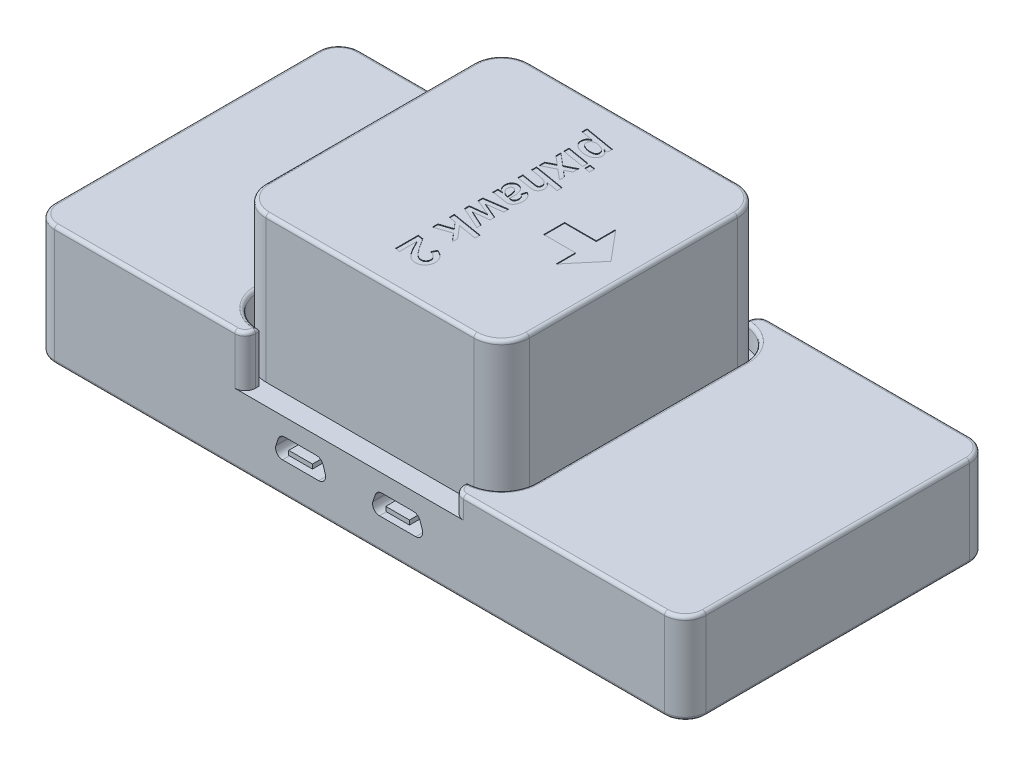
SolidWorks part; units mm, degrees
ref_plane "Front Plane" through (0, 0, 0) normal (0, 0, 1) x (1, 0, 0)
ref_plane "Top Plane" through (0, 0, 0) normal (0, 1, 0) x (1, 0, 0)
ref_plane "Right Plane" through (0, 0, 0) normal (1, 0, 0) x (0, 0, -1)
sketch "Sketch1" plane through (0, 0, 0) normal (0, 1, 0) x (1, 0, 0)
  line L1 (-44, 22) -> (44, 22)
  line L2 (-47, 19) -> (-47, -19)
  line L3 (-44, -22) -> (44, -22)
  line L4 (47, 19) -> (47, -19)
  line L5 (-47, 22) -> (47, -22) construction
  line L6 (-47, -22) -> (47, 22) construction
  arc A0 (44, 22) -> (47, 19) centre (44, 19) cw
  arc A1 (-47, -19) -> (-44, -22) centre (-44, -19) ccw
  arc A2 (-44, 22) -> (-47, 19) centre (-44, 19) ccw
  arc A3 (44, -22) -> (47, -19) centre (44, -19) ccw
  point P0 (0, 0)
  dimension "D3" = 3
  dimension "D1" = 94
  dimension "D2" = 44
extrude "Boss-Extrude1" add sketch "Sketch1" along normal blind 10
sketch "Sketch2" plane through (0, 10, 0) normal (0, 1, 0) x (1, 0, 0)
  line L1 (-16.5, 20) -> (13.5, 20)
  line L2 (-21.5, 15) -> (-21.5, -15)
  line L3 (-16.5, -20) -> (13.5, -20)
  line L4 (18.5, 15) -> (18.5, -15)
  line L5 (-21.5, 20) -> (18.5, -20) construction
  line L6 (-21.5, -20) -> (18.5, 20) construction
  line L7 (-47, 0) -> (0, 0) construction
  line L8 (-47, 19) -> (-47, -19) construction
  line L9 (0, 0) -> (0, 22) construction
  line L10 (44, 22) -> (-44, 22) construction
  arc A0 (13.5, 20) -> (18.5, 15) centre (13.5, 15) cw
  arc A1 (-21.5, -15) -> (-16.5, -20) centre (-16.5, -15) ccw
  arc A2 (-16.5, 20) -> (-21.5, 15) centre (-16.5, 15) ccw
  arc A3 (13.5, -20) -> (18.5, -15) centre (13.5, -15) ccw
  point P0 (-1.5, 0)
  dimension "D4" = 5
  dimension "D1" = 40
  dimension "D2" = 40
  dimension "D3" = 25.5
sketch "Sketch3" plane through (0, 10, 0) normal (0, 1, 0) x (1, 0, 0)
  line L0 (18.5, 15) -> (18.5, -15) construction
  line L1 (44, 22) -> (-44, 22) construction
  line L2 (47, -19) -> (47, 19) construction
  line L3 (-44, -22) -> (44, -22) construction
  line L4 (18.5, 15) -> (18.5, -15)
  line L5 (44, 22) -> (13.5, 22)
  line L6 (47, -19) -> (47, 19)
  line L7 (13.5, -22) -> (44, -22)
  line L8 (13.5, 20) -> (13.5, 22)
  line L9 (13.5, -20) -> (13.5, -22)
  arc A0 (18.5, 15) -> (13.5, 20) centre (13.5, 15) ccw construction
  arc A1 (13.5, -20) -> (18.5, -15) centre (13.5, -15) ccw construction
  arc A2 (47, 19) -> (44, 22) centre (44, 19) ccw construction
  arc A3 (44, -22) -> (47, -19) centre (44, -19) ccw construction
  arc A4 (18.5, 15) -> (13.5, 20) centre (13.5, 15) ccw
  arc A5 (13.5, -20) -> (18.5, -15) centre (13.5, -15) ccw
  arc A6 (47, 19) -> (44, 22) centre (44, 19) ccw
  arc A7 (44, -22) -> (47, -19) centre (44, -19) ccw
extrude "Boss-Extrude2" add sketch "Sketch3" along normal blind 3.1
sketch "Sketch4" plane through (0, 10, 0) normal (0, 1, 0) x (1, 0, 0)
  line L0 (-21.5, 15) -> (-21.5, -15) construction
  line L1 (-44, -22) -> (13.5, -22) construction
  line L2 (-47, 19) -> (-47, -19) construction
  line L3 (13.5, 22) -> (-44, 22) construction
  line L4 (-21.5, 15) -> (-21.5, -15)
  line L5 (-44, -22) -> (-16.5, -22)
  line L6 (-47, 19) -> (-47, -19)
  line L7 (-16.5, 22) -> (-44, 22)
  line L8 (-16.5, 20) -> (-16.5, 22)
  line L9 (-16.5, -20) -> (-16.5, -22)
  arc A0 (-16.5, 20) -> (-21.5, 15) centre (-16.5, 15) ccw construction
  arc A1 (-21.5, -15) -> (-16.5, -20) centre (-16.5, -15) ccw construction
  arc A2 (-47, -19) -> (-44, -22) centre (-44, -19) ccw construction
  arc A3 (-44, 22) -> (-47, 19) centre (-44, 19) ccw construction
  arc A4 (-16.5, 20) -> (-21.5, 15) centre (-16.5, 15) ccw
  arc A5 (-21.5, -15) -> (-16.5, -20) centre (-16.5, -15) ccw
  arc A6 (-47, -19) -> (-44, -22) centre (-44, -19) ccw
  arc A7 (-44, 22) -> (-47, 19) centre (-44, 19) ccw
extrude "Boss-Extrude3" add sketch "Sketch4" along normal blind 7.3
fillet "Fillet1" radius 1.5 4 edges at (-16.5, 13.65, -22) (-16.5, 13.65, 22)
sketch "Sketch5" plane through (0, 10, 0) normal (0, 1, 0) x (1, 0, 0)
  line L24 (-16.5, -19) -> (13.5, -19)
  line L25 (17.5, -15) -> (17.5, 15)
  line L26 (13.5, 19) -> (-16.5, 19)
  line L27 (-20.5, 15) -> (-20.5, -15)
  line L28 (-16.5, -19) -> (13.5, -19)
  line L29 (17.5, -15) -> (17.5, 15)
  line L30 (13.5, 19) -> (-16.5, 19)
  line L31 (-20.5, 15) -> (-20.5, -15)
  arc A20 (-20.5, -15) -> (-16.5, -19) centre (-16.5, -15) ccw
  arc A21 (13.5, -19) -> (17.5, -15) centre (13.5, -15) ccw
  arc A22 (17.5, 15) -> (13.5, 19) centre (13.5, 15) ccw
  arc A23 (-16.5, 19) -> (-20.5, 15) centre (-16.5, 15) ccw
  arc A24 (-20.5, -15) -> (-16.5, -19) centre (-16.5, -15) ccw
  arc A25 (13.5, -19) -> (17.5, -15) centre (13.5, -15) ccw
  arc A26 (17.5, 15) -> (13.5, 19) centre (13.5, 15) ccw
  arc A27 (-16.5, 19) -> (-20.5, 15) centre (-16.5, 15) ccw
  dimension "D1" = 1
extrude "Boss-Extrude4" add sketch "Sketch5" along normal blind 21
fillet "Fillet2" radius 0.5 40 edges at (0, 0, -22) (-46.1213, 0, -21.1213) (-47, 0, 0) (-46.1213, 0, 21.1213) (0, 0, 22) (46.1213, 0, 21.1213) (47, 0, 0) (46.1213, 0, -21.1213) (-20.0355, 17.3, -18.5355) (-21.5, 17.3, 0) (-20.0355, 17.3, 18.5355) (-16.5, 17.3, 20.25) (-16.9393, 17.3, 21.5607) (-31, 17.3, 22) (-46.1213, 17.3, 21.1213) (-47, 17.3, 0) (-46.1213, 17.3, -21.1213) (-31, 17.3, -22) (-16.9393, 17.3, -21.5607) (-16.5, 17.3, -20.25) (46.1213, 13.1, -21.1213) (47, 13.1, 0) (46.1213, 13.1, 21.1213) (29.5, 13.1, 22) (13.9393, 13.1, 21.5607) (13.5, 13.1, 20.25) (17.0355, 13.1, 18.5355) (18.5, 13.1, 0) (17.0355, 13.1, -18.5355) (13.5, 13.1, -20.25) (13.9393, 13.1, -21.5607) (29.5, 13.1, -22) (-20.5, 31, 0) (-19.3284, 31, -17.8284) (-1.5, 31, -19) (16.3284, 31, -17.8284) (17.5, 31, 0) (16.3284, 31, 17.8284) (-1.5, 31, 19) (-19.3284, 31, 17.8284)
sketch "Sketch6" plane through (-47, 0, 0) normal (-1, 0, 0) x (0, 0, 1)
  line L0 (-19, 16) -> (-19, 7.2)
  line L1 (-19, 7.2) -> (-18, 7.2)
  line L2 (-18, 7.2) -> (-18, 8)
  line L3 (-18, 8) -> (-17, 8)
  line L4 (-3, 8) -> (-3, 7.2)
  line L5 (-17, 16) -> (-19, 16)
  line L6 (-19, 17.3) -> (19, 17.3) construction
  line L7 (-22, 16.8) -> (-22, 0.5) construction
  line L8 (-17, 12) -> (-19, 12) construction
  line L9 (-18.375, 14.125) -> (-17.625, 14.125)
  line L10 (-18.375, 12.375) -> (-17.625, 12.375)
  line L11 (-18.375, 12.375) -> (-18.375, 11.625)
  line L12 (-18.375, 11.625) -> (-17.625, 11.625)
  line L13 (-17.625, 12.375) -> (-17.625, 11.625)
  line L14 (-18.375, 12.375) -> (-17.625, 11.625) construction
  line L15 (-18.375, 11.625) -> (-17.625, 12.375) construction
  line L16 (-18.375, 14.875) -> (-18.375, 14.125)
  line L17 (-18.375, 14.875) -> (-17.625, 14.875)
  line L18 (-17.625, 14.875) -> (-17.625, 14.125)
  line L19 (-17.625, 9.125) -> (-17.625, 9.875)
  line L20 (-18.375, 9.125) -> (-17.625, 9.125)
  line L21 (-18.375, 9.125) -> (-18.375, 9.875)
  line L22 (-18.375, 9.875) -> (-17.625, 9.875)
  line L23 (-1, 8) -> (-1, 7.2)
  line L24 (-17, 7.2) -> (-16, 7.2)
  line L25 (-16, 7.2) -> (-16, 8)
  line L26 (-16, 8) -> (-15, 8)
  line L27 (1, 8) -> (1, 7.2)
  line L28 (-15, 16) -> (-17, 16)
  line L29 (-16.375, 14.125) -> (-15.625, 14.125)
  line L30 (-16.375, 12.375) -> (-15.625, 12.375)
  line L31 (-16.375, 12.375) -> (-16.375, 11.625)
  line L32 (-16.375, 11.625) -> (-15.625, 11.625)
  line L33 (-15.625, 12.375) -> (-15.625, 11.625)
  line L34 (-16.375, 14.875) -> (-16.375, 14.125)
  line L35 (-16.375, 14.875) -> (-15.625, 14.875)
  line L36 (-15.625, 14.875) -> (-15.625, 14.125)
  line L37 (-15.625, 9.125) -> (-15.625, 9.875)
  line L38 (-16.375, 9.125) -> (-15.625, 9.125)
  line L39 (-16.375, 9.125) -> (-16.375, 9.875)
  line L40 (-16.375, 9.875) -> (-15.625, 9.875)
  line L41 (-15, 12) -> (-17, 12) construction
  line L42 (-16.375, 12.375) -> (-15.625, 11.625) construction
  line L43 (-16.375, 11.625) -> (-15.625, 12.375) construction
  line L44 (-15, 8) -> (-15, 7.2)
  line L45 (-15, 7.2) -> (-14, 7.2)
  line L46 (-14, 7.2) -> (-14, 8)
  line L47 (-14, 8) -> (-13, 8)
  line L48 (3, 8) -> (3, 7.2)
  line L49 (-13, 16) -> (-15, 16)
  line L50 (-14.375, 14.125) -> (-13.625, 14.125)
  line L51 (-14.375, 12.375) -> (-13.625, 12.375)
  line L52 (-14.375, 12.375) -> (-14.375, 11.625)
  line L53 (-14.375, 11.625) -> (-13.625, 11.625)
  line L54 (-13.625, 12.375) -> (-13.625, 11.625)
  line L55 (-14.375, 14.875) -> (-14.375, 14.125)
  line L56 (-14.375, 14.875) -> (-13.625, 14.875)
  line L57 (-13.625, 14.875) -> (-13.625, 14.125)
  line L58 (-13.625, 9.125) -> (-13.625, 9.875)
  line L59 (-14.375, 9.125) -> (-13.625, 9.125)
  line L60 (-14.375, 9.125) -> (-14.375, 9.875)
  line L61 (-14.375, 9.875) -> (-13.625, 9.875)
  line L62 (-13, 12) -> (-15, 12) construction
  line L63 (-14.375, 12.375) -> (-13.625, 11.625) construction
  line L64 (-14.375, 11.625) -> (-13.625, 12.375) construction
  line L65 (-13, 8) -> (-13, 7.2)
  line L66 (-13, 7.2) -> (-12, 7.2)
  line L67 (-12, 7.2) -> (-12, 8)
  line L68 (-12, 8) -> (-11, 8)
  line L69 (5, 8) -> (5, 7.2)
  line L70 (-11, 16) -> (-13, 16)
  line L71 (-12.375, 14.125) -> (-11.625, 14.125)
  line L72 (-12.375, 12.375) -> (-11.625, 12.375)
  line L73 (-12.375, 12.375) -> (-12.375, 11.625)
  line L74 (-12.375, 11.625) -> (-11.625, 11.625)
  line L75 (-11.625, 12.375) -> (-11.625, 11.625)
  line L76 (-12.375, 14.875) -> (-12.375, 14.125)
  line L77 (-12.375, 14.875) -> (-11.625, 14.875)
  line L78 (-11.625, 14.875) -> (-11.625, 14.125)
  line L79 (-11.625, 9.125) -> (-11.625, 9.875)
  line L80 (-12.375, 9.125) -> (-11.625, 9.125)
  line L81 (-12.375, 9.125) -> (-12.375, 9.875)
  line L82 (-12.375, 9.875) -> (-11.625, 9.875)
  line L83 (-11, 12) -> (-13, 12) construction
  line L84 (-12.375, 12.375) -> (-11.625, 11.625) construction
  line L85 (-12.375, 11.625) -> (-11.625, 12.375) construction
  line L86 (-11, 8) -> (-11, 7.2)
  line L87 (-11, 7.2) -> (-10, 7.2)
  line L88 (-10, 7.2) -> (-10, 8)
  line L89 (-10, 8) -> (-9, 8)
  line L90 (7, 8) -> (7, 7.2)
  line L91 (-9, 16) -> (-11, 16)
  line L92 (-10.375, 14.125) -> (-9.625, 14.125)
  line L93 (-10.375, 12.375) -> (-9.625, 12.375)
  line L94 (-10.375, 12.375) -> (-10.375, 11.625)
  line L95 (-10.375, 11.625) -> (-9.625, 11.625)
  line L96 (-9.625, 12.375) -> (-9.625, 11.625)
  line L97 (-10.375, 14.875) -> (-10.375, 14.125)
  line L98 (-10.375, 14.875) -> (-9.625, 14.875)
  line L99 (-9.625, 14.875) -> (-9.625, 14.125)
  line L100 (-9.625, 9.125) -> (-9.625, 9.875)
  line L101 (-10.375, 9.125) -> (-9.625, 9.125)
  line L102 (-10.375, 9.125) -> (-10.375, 9.875)
  line L103 (-10.375, 9.875) -> (-9.625, 9.875)
  line L104 (-9, 12) -> (-11, 12) construction
  line L105 (-10.375, 12.375) -> (-9.625, 11.625) construction
  line L106 (-10.375, 11.625) -> (-9.625, 12.375) construction
  line L107 (-9, 8) -> (-9, 7.2)
  line L108 (-9, 7.2) -> (-8, 7.2)
  line L109 (-8, 7.2) -> (-8, 8)
  line L110 (-8, 8) -> (-7, 8)
  line L111 (9, 8) -> (9, 7.2)
  line L112 (-7, 16) -> (-9, 16)
  line L113 (-8.375, 14.125) -> (-7.625, 14.125)
  line L114 (-8.375, 12.375) -> (-7.625, 12.375)
  line L115 (-8.375, 12.375) -> (-8.375, 11.625)
  line L116 (-8.375, 11.625) -> (-7.625, 11.625)
  line L117 (-7.625, 12.375) -> (-7.625, 11.625)
  line L118 (-8.375, 14.875) -> (-8.375, 14.125)
  line L119 (-8.375, 14.875) -> (-7.625, 14.875)
  line L120 (-7.625, 14.875) -> (-7.625, 14.125)
  line L121 (-7.625, 9.125) -> (-7.625, 9.875)
  line L122 (-8.375, 9.125) -> (-7.625, 9.125)
  line L123 (-8.375, 9.125) -> (-8.375, 9.875)
  line L124 (-8.375, 9.875) -> (-7.625, 9.875)
  line L125 (-7, 12) -> (-9, 12) construction
  line L126 (-8.375, 12.375) -> (-7.625, 11.625) construction
  line L127 (-8.375, 11.625) -> (-7.625, 12.375) construction
  line L128 (-7, 8) -> (-7, 7.2)
  line L129 (-7, 7.2) -> (-6, 7.2)
  line L130 (-6, 7.2) -> (-6, 8)
  line L131 (-6, 8) -> (-5, 8)
  line L132 (11, 8) -> (11, 7.2)
  line L133 (-5, 16) -> (-7, 16)
  line L134 (-6.375, 14.125) -> (-5.625, 14.125)
  line L135 (-6.375, 12.375) -> (-5.625, 12.375)
  line L136 (-6.375, 12.375) -> (-6.375, 11.625)
  line L137 (-6.375, 11.625) -> (-5.625, 11.625)
  line L138 (-5.625, 12.375) -> (-5.625, 11.625)
  line L139 (-6.375, 14.875) -> (-6.375, 14.125)
  line L140 (-6.375, 14.875) -> (-5.625, 14.875)
  line L141 (-5.625, 14.875) -> (-5.625, 14.125)
  line L142 (-5.625, 9.125) -> (-5.625, 9.875)
  line L143 (-6.375, 9.125) -> (-5.625, 9.125)
  line L144 (-6.375, 9.125) -> (-6.375, 9.875)
  line L145 (-6.375, 9.875) -> (-5.625, 9.875)
  line L146 (-5, 12) -> (-7, 12) construction
  line L147 (-6.375, 12.375) -> (-5.625, 11.625) construction
  line L148 (-6.375, 11.625) -> (-5.625, 12.375) construction
  line L149 (-5, 8) -> (-5, 7.2)
  line L150 (-5, 7.2) -> (-4, 7.2)
  line L151 (-4, 7.2) -> (-4, 8)
  line L152 (-4, 8) -> (-3, 8)
  line L154 (-3, 16) -> (-5, 16)
  line L155 (-4.375, 14.125) -> (-3.625, 14.125)
  line L156 (-4.375, 12.375) -> (-3.625, 12.375)
  line L157 (-4.375, 12.375) -> (-4.375, 11.625)
  line L158 (-4.375, 11.625) -> (-3.625, 11.625)
  line L159 (-3.625, 12.375) -> (-3.625, 11.625)
  line L160 (-4.375, 14.875) -> (-4.375, 14.125)
  line L161 (-4.375, 14.875) -> (-3.625, 14.875)
  line L162 (-3.625, 14.875) -> (-3.625, 14.125)
  line L163 (-3.625, 9.125) -> (-3.625, 9.875)
  line L164 (-4.375, 9.125) -> (-3.625, 9.125)
  line L165 (-4.375, 9.125) -> (-4.375, 9.875)
  line L166 (-4.375, 9.875) -> (-3.625, 9.875)
  line L167 (-3, 12) -> (-5, 12) construction
  line L168 (-4.375, 12.375) -> (-3.625, 11.625) construction
  line L169 (-4.375, 11.625) -> (-3.625, 12.375) construction
  line L171 (-3, 7.2) -> (-2, 7.2)
  line L172 (-2, 7.2) -> (-2, 8)
  line L173 (-2, 8) -> (-1, 8)
  line L175 (-1, 16) -> (-3, 16)
  line L176 (-2.375, 14.125) -> (-1.625, 14.125)
  line L177 (-2.375, 12.375) -> (-1.625, 12.375)
  line L178 (-2.375, 12.375) -> (-2.375, 11.625)
  line L179 (-2.375, 11.625) -> (-1.625, 11.625)
  line L180 (-1.625, 12.375) -> (-1.625, 11.625)
  line L181 (-2.375, 14.875) -> (-2.375, 14.125)
  line L182 (-2.375, 14.875) -> (-1.625, 14.875)
  line L183 (-1.625, 14.875) -> (-1.625, 14.125)
  line L184 (-1.625, 9.125) -> (-1.625, 9.875)
  line L185 (-2.375, 9.125) -> (-1.625, 9.125)
  line L186 (-2.375, 9.125) -> (-2.375, 9.875)
  line L187 (-2.375, 9.875) -> (-1.625, 9.875)
  line L188 (-1, 12) -> (-3, 12) construction
  line L189 (-2.375, 12.375) -> (-1.625, 11.625) construction
  line L190 (-2.375, 11.625) -> (-1.625, 12.375) construction
  line L192 (-1, 7.2) -> (0, 7.2)
  line L193 (0, 7.2) -> (0, 8)
  line L194 (0, 8) -> (1, 8)
  line L196 (1, 16) -> (-1, 16)
  line L197 (-0.375, 14.125) -> (0.375, 14.125)
  line L198 (-0.375, 12.375) -> (0.375, 12.375)
  line L199 (-0.375, 12.375) -> (-0.375, 11.625)
  line L200 (-0.375, 11.625) -> (0.375, 11.625)
  line L201 (0.375, 12.375) -> (0.375, 11.625)
  line L202 (-0.375, 14.875) -> (-0.375, 14.125)
  line L203 (-0.375, 14.875) -> (0.375, 14.875)
  line L204 (0.375, 14.875) -> (0.375, 14.125)
  line L205 (0.375, 9.125) -> (0.375, 9.875)
  line L206 (-0.375, 9.125) -> (0.375, 9.125)
  line L207 (-0.375, 9.125) -> (-0.375, 9.875)
  line L208 (-0.375, 9.875) -> (0.375, 9.875)
  line L209 (1, 12) -> (-1, 12) construction
  line L210 (-0.375, 12.375) -> (0.375, 11.625) construction
  line L211 (-0.375, 11.625) -> (0.375, 12.375) construction
  line L213 (1, 7.2) -> (2, 7.2)
  line L214 (2, 7.2) -> (2, 8)
  line L215 (2, 8) -> (3, 8)
  line L217 (3, 16) -> (1, 16)
  line L218 (1.625, 14.125) -> (2.375, 14.125)
  line L219 (1.625, 12.375) -> (2.375, 12.375)
  line L220 (1.625, 12.375) -> (1.625, 11.625)
  line L221 (1.625, 11.625) -> (2.375, 11.625)
  line L222 (2.375, 12.375) -> (2.375, 11.625)
  line L223 (1.625, 14.875) -> (1.625, 14.125)
  line L224 (1.625, 14.875) -> (2.375, 14.875)
  line L225 (2.375, 14.875) -> (2.375, 14.125)
  line L226 (2.375, 9.125) -> (2.375, 9.875)
  line L227 (1.625, 9.125) -> (2.375, 9.125)
  line L228 (1.625, 9.125) -> (1.625, 9.875)
  line L229 (1.625, 9.875) -> (2.375, 9.875)
  line L230 (3, 12) -> (1, 12) construction
  line L231 (1.625, 12.375) -> (2.375, 11.625) construction
  line L232 (1.625, 11.625) -> (2.375, 12.375) construction
  line L234 (3, 7.2) -> (4, 7.2)
  line L235 (4, 7.2) -> (4, 8)
  line L236 (4, 8) -> (5, 8)
  line L238 (5, 16) -> (3, 16)
  line L239 (3.625, 14.125) -> (4.375, 14.125)
  line L240 (3.625, 12.375) -> (4.375, 12.375)
  line L241 (3.625, 12.375) -> (3.625, 11.625)
  line L242 (3.625, 11.625) -> (4.375, 11.625)
  line L243 (4.375, 12.375) -> (4.375, 11.625)
  line L244 (3.625, 14.875) -> (3.625, 14.125)
  line L245 (3.625, 14.875) -> (4.375, 14.875)
  line L246 (4.375, 14.875) -> (4.375, 14.125)
  line L247 (4.375, 9.125) -> (4.375, 9.875)
  line L248 (3.625, 9.125) -> (4.375, 9.125)
  line L249 (3.625, 9.125) -> (3.625, 9.875)
  line L250 (3.625, 9.875) -> (4.375, 9.875)
  line L251 (5, 12) -> (3, 12) construction
  line L252 (3.625, 12.375) -> (4.375, 11.625) construction
  line L253 (3.625, 11.625) -> (4.375, 12.375) construction
  line L255 (5, 7.2) -> (6, 7.2)
  line L256 (6, 7.2) -> (6, 8)
  line L257 (6, 8) -> (7, 8)
  line L259 (7, 16) -> (5, 16)
  line L260 (5.625, 14.125) -> (6.375, 14.125)
  line L261 (5.625, 12.375) -> (6.375, 12.375)
  line L262 (5.625, 12.375) -> (5.625, 11.625)
  line L263 (5.625, 11.625) -> (6.375, 11.625)
  line L264 (6.375, 12.375) -> (6.375, 11.625)
  line L265 (5.625, 14.875) -> (5.625, 14.125)
  line L266 (5.625, 14.875) -> (6.375, 14.875)
  line L267 (6.375, 14.875) -> (6.375, 14.125)
  line L268 (6.375, 9.125) -> (6.375, 9.875)
  line L269 (5.625, 9.125) -> (6.375, 9.125)
  line L270 (5.625, 9.125) -> (5.625, 9.875)
  line L271 (5.625, 9.875) -> (6.375, 9.875)
  line L272 (7, 12) -> (5, 12) construction
  line L273 (5.625, 12.375) -> (6.375, 11.625) construction
  line L274 (5.625, 11.625) -> (6.375, 12.375) construction
  line L276 (7, 7.2) -> (8, 7.2)
  line L277 (8, 7.2) -> (8, 8)
  line L278 (8, 8) -> (9, 8)
  line L280 (9, 16) -> (7, 16)
  line L281 (7.625, 14.125) -> (8.375, 14.125)
  line L282 (7.625, 12.375) -> (8.375, 12.375)
  line L283 (7.625, 12.375) -> (7.625, 11.625)
  line L284 (7.625, 11.625) -> (8.375, 11.625)
  line L285 (8.375, 12.375) -> (8.375, 11.625)
  line L286 (7.625, 14.875) -> (7.625, 14.125)
  line L287 (7.625, 14.875) -> (8.375, 14.875)
  line L288 (8.375, 14.875) -> (8.375, 14.125)
  line L289 (8.375, 9.125) -> (8.375, 9.875)
  line L290 (7.625, 9.125) -> (8.375, 9.125)
  line L291 (7.625, 9.125) -> (7.625, 9.875)
  line L292 (7.625, 9.875) -> (8.375, 9.875)
  line L293 (9, 12) -> (7, 12) construction
  line L294 (7.625, 12.375) -> (8.375, 11.625) construction
  line L295 (7.625, 11.625) -> (8.375, 12.375) construction
  line L297 (9, 7.2) -> (10, 7.2)
  line L298 (10, 7.2) -> (10, 8)
  line L299 (10, 8) -> (11, 8)
  line L301 (11, 16) -> (9, 16)
  line L302 (9.625, 14.125) -> (10.375, 14.125)
  line L303 (9.625, 12.375) -> (10.375, 12.375)
  line L304 (9.625, 12.375) -> (9.625, 11.625)
  line L305 (9.625, 11.625) -> (10.375, 11.625)
  line L306 (10.375, 12.375) -> (10.375, 11.625)
  line L307 (9.625, 14.875) -> (9.625, 14.125)
  line L308 (9.625, 14.875) -> (10.375, 14.875)
  line L309 (10.375, 14.875) -> (10.375, 14.125)
  line L310 (10.375, 9.125) -> (10.375, 9.875)
  line L311 (9.625, 9.125) -> (10.375, 9.125)
  line L312 (9.625, 9.125) -> (9.625, 9.875)
  line L313 (9.625, 9.875) -> (10.375, 9.875)
  line L314 (11, 12) -> (9, 12) construction
  line L315 (9.625, 12.375) -> (10.375, 11.625) construction
  line L316 (9.625, 11.625) -> (10.375, 12.375) construction
  line L318 (11, 7.2) -> (12, 7.2)
  line L319 (12, 7.2) -> (12, 8)
  line L320 (12, 8) -> (13, 8)
  line L322 (13, 16) -> (11, 16)
  line L323 (11.625, 14.125) -> (12.375, 14.125)
  line L324 (11.625, 12.375) -> (12.375, 12.375)
  line L325 (11.625, 12.375) -> (11.625, 11.625)
  line L326 (11.625, 11.625) -> (12.375, 11.625)
  line L327 (12.375, 12.375) -> (12.375, 11.625)
  line L328 (11.625, 14.875) -> (11.625, 14.125)
  line L329 (11.625, 14.875) -> (12.375, 14.875)
  line L330 (12.375, 14.875) -> (12.375, 14.125)
  line L331 (12.375, 9.125) -> (12.375, 9.875)
  line L332 (11.625, 9.125) -> (12.375, 9.125)
  line L333 (11.625, 9.125) -> (11.625, 9.875)
  line L334 (11.625, 9.875) -> (12.375, 9.875)
  line L335 (13, 12) -> (11, 12) construction
  line L336 (11.625, 12.375) -> (12.375, 11.625) construction
  line L337 (11.625, 11.625) -> (12.375, 12.375) construction
  line L339 (13, 7.2) -> (14, 7.2)
  line L340 (14, 7.2) -> (14, 8)
  line L341 (14, 8) -> (15, 8)
  line L343 (15, 16) -> (13, 16)
  line L344 (13.625, 14.125) -> (14.375, 14.125)
  line L345 (13.625, 12.375) -> (14.375, 12.375)
  line L346 (13.625, 12.375) -> (13.625, 11.625)
  line L347 (13.625, 11.625) -> (14.375, 11.625)
  line L348 (14.375, 12.375) -> (14.375, 11.625)
  line L349 (13.625, 14.875) -> (13.625, 14.125)
  line L350 (13.625, 14.875) -> (14.375, 14.875)
  line L351 (14.375, 14.875) -> (14.375, 14.125)
  line L352 (14.375, 9.125) -> (14.375, 9.875)
  line L353 (13.625, 9.125) -> (14.375, 9.125)
  line L354 (13.625, 9.125) -> (13.625, 9.875)
  line L355 (13.625, 9.875) -> (14.375, 9.875)
  line L356 (15, 12) -> (13, 12) construction
  line L357 (13.625, 12.375) -> (14.375, 11.625) construction
  line L358 (13.625, 11.625) -> (14.375, 12.375) construction
  line L359 (15, 8) -> (15, 7.2)
  line L360 (15, 7.2) -> (16, 7.2)
  line L361 (16, 7.2) -> (16, 8)
  line L362 (16, 8) -> (17, 8)
  line L364 (17, 16) -> (15, 16)
  line L365 (15.625, 14.125) -> (16.375, 14.125)
  line L366 (15.625, 12.375) -> (16.375, 12.375)
  line L367 (15.625, 12.375) -> (15.625, 11.625)
  line L368 (15.625, 11.625) -> (16.375, 11.625)
  line L369 (16.375, 12.375) -> (16.375, 11.625)
  line L370 (15.625, 14.875) -> (15.625, 14.125)
  line L371 (15.625, 14.875) -> (16.375, 14.875)
  line L372 (16.375, 14.875) -> (16.375, 14.125)
  line L373 (16.375, 9.125) -> (16.375, 9.875)
  line L374 (15.625, 9.125) -> (16.375, 9.125)
  line L375 (15.625, 9.125) -> (15.625, 9.875)
  line L376 (15.625, 9.875) -> (16.375, 9.875)
  line L377 (17, 12) -> (15, 12) construction
  line L378 (15.625, 12.375) -> (16.375, 11.625) construction
  line L379 (15.625, 11.625) -> (16.375, 12.375) construction
  line L380 (17, 8) -> (17, 7.2)
  line L381 (17, 7.2) -> (18, 7.2)
  line L382 (18, 7.2) -> (18, 8)
  line L383 (18, 8) -> (19, 8)
  line L384 (19, 8) -> (19, 16)
  line L385 (19, 16) -> (17, 16)
  line L386 (17.625, 14.125) -> (18.375, 14.125)
  line L387 (17.625, 12.375) -> (18.375, 12.375)
  line L388 (17.625, 12.375) -> (17.625, 11.625)
  line L389 (17.625, 11.625) -> (18.375, 11.625)
  line L390 (18.375, 12.375) -> (18.375, 11.625)
  line L391 (17.625, 14.875) -> (17.625, 14.125)
  line L392 (17.625, 14.875) -> (18.375, 14.875)
  line L393 (18.375, 14.875) -> (18.375, 14.125)
  line L394 (18.375, 9.125) -> (18.375, 9.875)
  line L395 (17.625, 9.125) -> (18.375, 9.125)
  line L396 (17.625, 9.125) -> (17.625, 9.875)
  line L397 (17.625, 9.875) -> (18.375, 9.875)
  line L398 (19, 12) -> (17, 12) construction
  line L399 (17.625, 12.375) -> (18.375, 11.625) construction
  line L400 (17.625, 11.625) -> (18.375, 12.375) construction
  line L401 (-17, 8) -> (-17, 7.2)
  line L402 (-17, 16) -> (-17, 12) [skipped]
  line L403 (13, 8) -> (13, 7.2)
  line L404 (-3, 16) -> (-3, 12) [skipped]
  line L405 (-1, 16) -> (-1, 12) [skipped]
  line L406 (1, 16) -> (1, 12) [skipped]
  line L407 (3, 16) -> (3, 12) [skipped]
  line L408 (5, 16) -> (5, 12) [skipped]
  line L409 (7, 16) -> (7, 12) [skipped]
  line L410 (9, 16) -> (9, 12) [skipped]
  line L411 (11, 16) -> (11, 12) [skipped]
  line L412 (13, 16) -> (13, 12) [skipped]
  point P12 (-18, 12)
  point P34 (-16, 12)
  point P55 (-14, 12)
  point P76 (-12, 12)
  point P97 (-10, 12)
  point P118 (-8, 12)
  point P139 (-6, 12)
  point P160 (-4, 12)
  point P181 (-2, 12)
  point P202 (0, 12)
  point P223 (2, 12)
  point P244 (4, 12)
  point P265 (6, 12)
  point P286 (8, 12)
  point P307 (10, 12)
  point P328 (12, 12)
  point P349 (14, 12)
  point P370 (16, 12)
  point P391 (18, 12)
  dimension "D1" = 2
  dimension "D2" = 1
  dimension "D3" = 8.8
  dimension "D4" = 0.8
  dimension "D5" = 1.3
  dimension "D6" = 3
  dimension "D7" = 0.75
  dimension "D8" = 0.75
  dimension "D9" = 2
  dimension "D10" = 19
extrude "Cut-Extrude1" cut sketch "Sketch6" against normal blind 8
sketch "Sketch7" plane through (0, 0, -19) normal (0, 0, -1) x (-1, 0, 0)
  line L0 (1.5, 30.5) -> (1.5, 10) construction
  line L1 (16.5, 30.5) -> (-13.5, 30.5) construction
  line L2 (-13.5, 10) -> (16.5, 10) construction
  line L3 (3.7792, 14) -> (-0.7792, 14)
  line L4 (-1.7279, 14.6838) -> (-2.0613, 15.6838)
  line L5 (-1.1126, 17) -> (4.1126, 17)
  line L6 (4.7279, 14.6838) -> (5.0613, 15.6838)
  line L8 (-0.7792, 15.6761) -> (3.7792, 15.6761)
  line L9 (-0.7792, 15.6761) -> (-0.7792, 14.858)
  line L10 (-0.7792, 14.858) -> (3.7792, 14.858)
  line L11 (3.7792, 15.6761) -> (3.7792, 14.858)
  line L12 (-0.7792, 15.6761) -> (3.7792, 14.858) construction
  line L13 (-0.7792, 14.858) -> (3.7792, 15.6761) construction
  arc A0 (4.7279, 14.6838) -> (3.7792, 14) centre (3.7792, 15) cw
  arc A1 (-2.0613, 15.6838) -> (-1.1126, 17) centre (-1.1126, 16) cw
  arc A2 (5.0613, 15.6838) -> (4.1126, 17) centre (4.1126, 16) ccw
  arc A3 (-0.7792, 14) -> (-1.7279, 14.6838) centre (-0.7792, 15) cw
  point P11 (1.5, 17)
  point P12 (1.5, 14)
  point P14 (4.5, 14)
  point P17 (-2.5, 17)
  point P20 (5.5, 17)
  point P23 (-1.5, 14)
  point P24 (1.5, 15.267)
  dimension "D5" = 1
  dimension "D1" = 4
  dimension "D2" = 3
  dimension "D3" = 4
  dimension "D4" = 3
extrude "Cut-Extrude2" cut sketch "Sketch7" against normal blind 5
sketch "Sketch8" plane through (0, 0, 22) normal (0, 0, 1) x (1, 0, 0)
  line L0 (-1.5, 31) -> (-1.5, 0) construction
  line L1 (-16.5, 31) -> (13.5, 31) construction
  line L2 (44, 0) -> (-44, 0) construction
  line L3 (-8.5, 0) -> (-8.5, 7.8311) construction
  line L4 (-6.2208, 7.5) -> (-10.7792, 7.5)
  line L5 (-11.7279, 6.8162) -> (-12.0613, 5.8162)
  line L6 (-11.1126, 4.5) -> (-5.8874, 4.5)
  line L7 (-5.2721, 6.8162) -> (-4.9387, 5.8162)
  line L8 (7.2118, 5.5) -> (3.7882, 6.1325) construction
  line L9 (-10.2118, 6.1325) -> (-6.7882, 6.1325)
  line L10 (-10.2118, 6.1325) -> (-10.2118, 5.5)
  line L11 (-10.2118, 5.5) -> (-6.7882, 5.5)
  line L12 (-6.7882, 6.1325) -> (-6.7882, 5.5)
  line L13 (-10.2118, 6.1325) -> (-6.7882, 5.5) construction
  line L14 (-10.2118, 5.5) -> (-6.7882, 6.1325) construction
  line L15 (7.2118, 6.1325) -> (3.7882, 5.5) construction
  line L16 (3.7882, 6.1325) -> (3.7882, 5.5)
  line L17 (7.2118, 5.5) -> (3.7882, 5.5)
  line L18 (7.2118, 6.1325) -> (7.2118, 5.5)
  line L19 (7.2118, 6.1325) -> (3.7882, 6.1325)
  line L20 (2.2721, 6.8162) -> (1.9387, 5.8162)
  line L21 (8.1126, 4.5) -> (2.8874, 4.5)
  line L22 (8.7279, 6.8162) -> (9.0613, 5.8162)
  line L23 (3.2208, 7.5) -> (7.7792, 7.5)
  arc A0 (-5.2721, 6.8162) -> (-6.2208, 7.5) centre (-6.2208, 6.5) ccw
  arc A1 (-12.0613, 5.8162) -> (-11.1126, 4.5) centre (-11.1126, 5.5) ccw
  arc A2 (-4.9387, 5.8162) -> (-5.8874, 4.5) centre (-5.8874, 5.5) cw
  arc A3 (-10.7792, 7.5) -> (-11.7279, 6.8162) centre (-10.7792, 6.5) ccw
  arc A4 (7.7792, 7.5) -> (8.7279, 6.8162) centre (7.7792, 6.5) cw
  arc A5 (1.9387, 5.8162) -> (2.8874, 4.5) centre (2.8874, 5.5) ccw
  arc A6 (9.0613, 5.8162) -> (8.1126, 4.5) centre (8.1126, 5.5) cw
  arc A7 (2.2721, 6.8162) -> (3.2208, 7.5) centre (3.2208, 6.5) cw
  point P13 (-8.5, 4.5)
  point P14 (-8.5, 7.5)
  point P16 (-5.5, 7.5)
  point P19 (-12.5, 4.5)
  point P22 (-4.5, 4.5)
  point P25 (-11.5, 7.5)
  point P26 (-8.5, 5.8162)
  point P47 (5.5, 5.8162)
  point P48 (8.5, 7.5)
  point P49 (1.5, 4.5)
  point P50 (9.5, 4.5)
  point P51 (2.5, 7.5)
  point P52 (5.5, 7.5)
  point P53 (5.5, 4.5)
  dimension "D5" = 1
  dimension "D1" = 4
  dimension "D2" = 3
  dimension "D3" = 3
  dimension "D4" = 4.5
  dimension "D6" = 7
extrude "Cut-Extrude3" cut sketch "Sketch8" against normal blind 5
sketch "Sketch9" plane through (0, 31, 0) normal (0, 1, 0) x (1, 0, 0)
  line L0 (-2.8759, 14.7991) -> (-2.8759, -11.5636) construction
  line L1 (0, 0) -> (17, 0) construction
  line L2 (17, -15) -> (17, 15) construction
  line L3 (14.2787, 0) -> (10.6568, 4.3164)
  line L4 (10.6568, 4.3164) -> (10.6568, 1.5)
  line L5 (10.6568, 1.5) -> (6.0895, 1.5)
  line L6 (6.0895, 1.5) -> (6.0895, -1.5)
  line L7 (10.6568, -1.5) -> (6.0895, -1.5)
  line L8 (10.6568, -4.3164) -> (10.6568, -1.5)
  line L9 (14.2787, 0) -> (10.6568, -4.3164)
  text T0 "pixhawk 2" font "Franklin Gothic Medium" height in points 18
  point P12 (6.0895, 0)
  dimension "D1" = 50
  dimension "D2" = 3
extrude "Cut-Extrude4" cut sketch "Sketch9" against normal blind 0.1
sketch "Sketch10" plane through (0, 0, 0) normal (0, -1, 0) x (1, 0, 0)
  line L0 (44, -22) -> (-44, -22) construction
  line L1 (43.25, -17.075) -> (-41.75, -17.075) construction
  line L2 (43.25, -17.075) -> (43.25, 17.325) construction
  line L3 (43.25, 17.325) -> (-41.75, 17.325) construction
  line L4 (-41.75, -17.075) -> (-41.75, 17.325) construction
  line L5 (-46.5, 19) -> (-46.5, -19) construction
  circle A0 centre (43.25, -17.075) radius 1.25
  circle A1 centre (43.25, 17.325) radius 1.25
  circle A2 centre (-41.75, -17.075) radius 1.25
  circle A3 centre (-41.75, 17.325) radius 1.25
  dimension "D1" = 85
  dimension "D2" = 34.4
  dimension "D3" = 4.925
  dimension "D4" = 4.75
extrude "Cut-Extrude5" cut sketch "Sketch10" against normal blind 4
